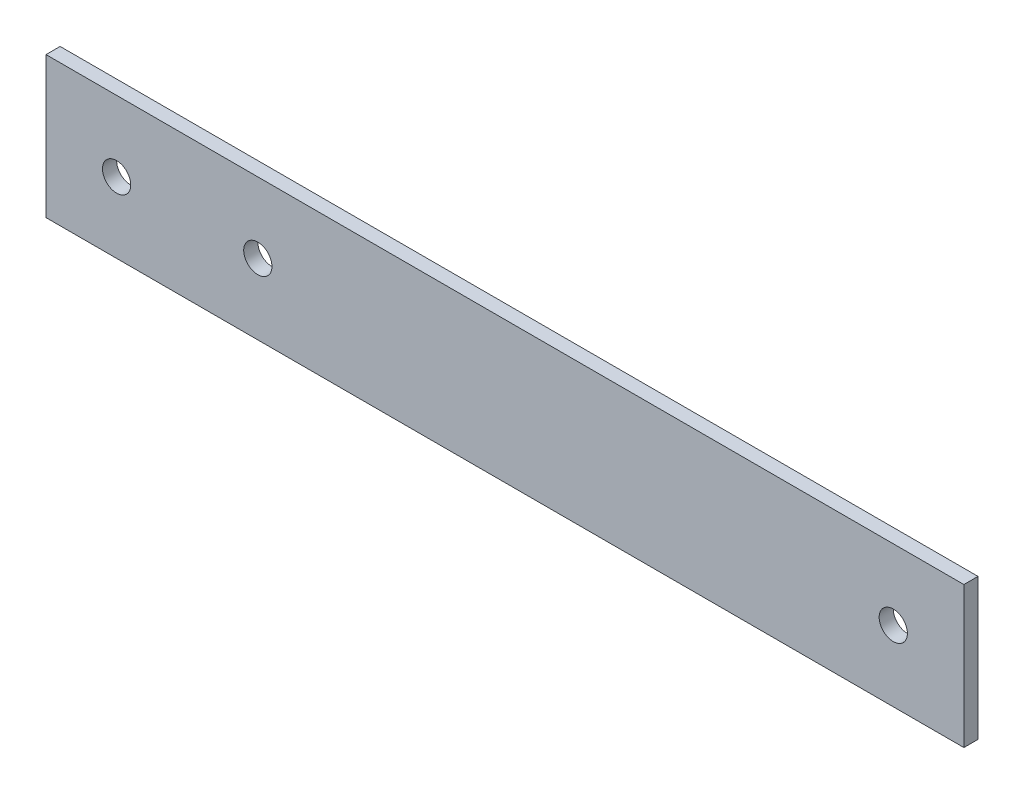
SolidWorks part; units mm, degrees
ref_plane "Front Plane" through (0, 0, 0) normal (0, 0, 1) x (1, 0, 0)
ref_plane "Top Plane" through (0, 0, 0) normal (0, 1, 0) x (1, 0, 0)
ref_plane "Right Plane" through (0, 0, 0) normal (1, 0, 0) x (0, 0, -1)
sketch "Sketch1" plane through (0, 0, 0) normal (0, 0, 1) x (1, 0, 0)
  line L1 (-65, 10) -> (65, 10)
  line L2 (-65, 10) -> (-65, -10)
  line L3 (-65, -10) -> (65, -10)
  line L4 (65, 10) -> (65, -10)
  line L5 (-65, 10) -> (65, -10) construction
  line L6 (-65, -10) -> (65, 10) construction
  point P0 (0, 0)
  dimension "D1" = 130
  dimension "D2" = 20
extrude "Boss-Extrude1" add sketch "Sketch1" along normal blind 2
sketch "Sketch2" plane through (0, 0, 2) normal (0, 0, 1) x (1, 0, 0)
  line L0 (65, -10) -> (65, 10) construction
  line L1 (-65, -10) -> (65, -10) construction
  line L2 (65, 10) -> (-65, 10) construction
  line L3 (-65, 10) -> (-65, -10) construction
  circle A0 centre (-55, 0) radius 2
  circle A1 centre (55, 0) radius 2
  dimension "D1" = 4
  dimension "D2" = 4
  dimension "D3" = 10
  dimension "D4" = 10
  dimension "D5" = 10
  dimension "D6" = 10
extrude "Cut-Extrude1" cut sketch "Sketch2" against normal blind 2
sketch "Sketch3" plane through (0, 0, 2) normal (0, 0, 1) x (1, 0, 0)
  line L0 (65, -10) -> (65, 10) construction
  circle A0 centre (-35, 0) radius 2
  dimension "D1" = 4
  dimension "D2" = 100
extrude "Cut-Extrude2" cut sketch "Sketch3" against normal blind 2
